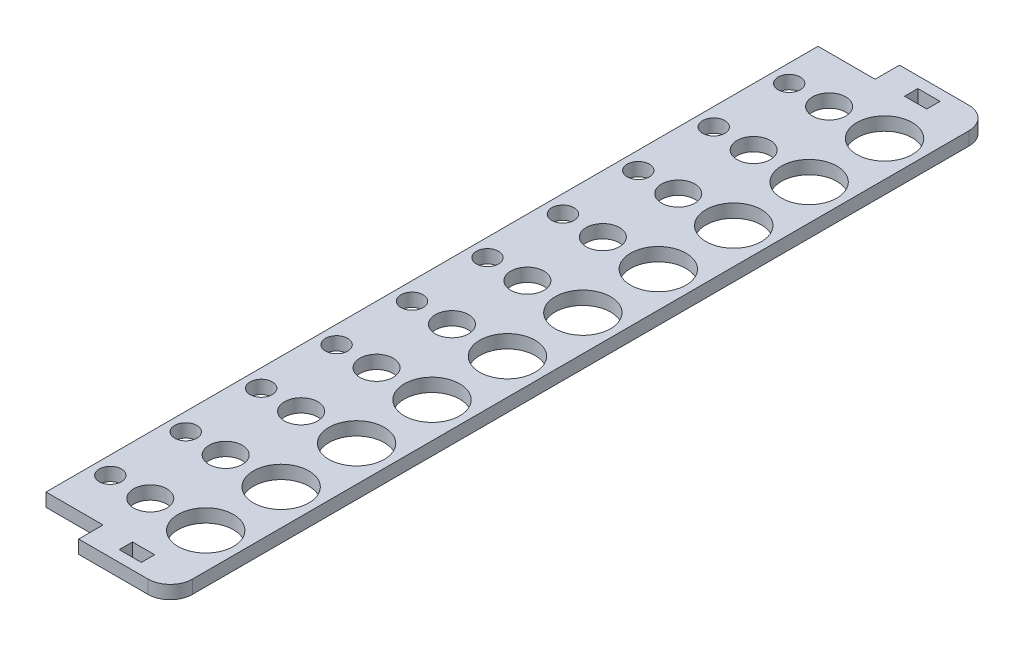
SolidWorks part; units mm, degrees
ref_plane "Plan de face" through (0, 0, 0) normal (0, 0, 1) x (1, 0, 0)
ref_plane "Plan de dessus" through (0, 0, 0) normal (0, 1, 0) x (1, 0, 0)
ref_plane "Plan de droite" through (0, 0, 0) normal (1, 0, 0) x (0, 0, -1)
sketch "Esquisse1" plane through (0, 0, 0) normal (0, 1, 0) x (1, 0, 0)
  line L0 (0, 185) -> (67, 185) construction
  line L1 (0, 11) -> (0, 359)
  line L2 (25.7287, 0) -> (67, 0)
  line L3 (25.7287, 370) -> (67, 370)
  line L4 (67, 0) -> (67, 370)
  line L5 (39, 365) -> (49, 365)
  line L6 (39, 365) -> (39, 359)
  line L7 (39, 359) -> (49, 359)
  line L8 (49, 365) -> (49, 359)
  line L9 (49, 5) -> (49, 11)
  line L10 (39, 11) -> (49, 11)
  line L11 (39, 5) -> (39, 11)
  line L12 (39, 5) -> (49, 5)
  line L13 (25.7287, 370) -> (25.7287, 359)
  line L14 (25.7287, 359) -> (0, 359)
  line L15 (67, 370) -> (66.5533, 370.0668)
  line L16 (25.7287, 0) -> (25.7287, 11)
  line L17 (25.7287, 11) -> (0, 11)
  dimension "D1" = 370
  dimension "D2" = 5
  dimension "D3" = 10
  dimension "D4" = 6
  dimension "D5" = 18
  dimension "D6" = 11
extrude "Boss.-Extru.1" add sketch "Esquisse1" along normal blind 6 contours L1 L0 L4 L3 L13 L14 L5 L8 L7 L6 | L0 L1 L17 L16 L2 L4 L12 L11 L10 L9
sketch "Esquisse2" plane through (0, 6, 0) normal (0, 1, 0) x (1, 0, 0)
  line L0 (67, 0) -> (67, 370) construction
  line L1 (25.7287, 370) -> (67, 370) construction
  line L5 (25.7287, 0) -> (67, 0) construction
  circle A0 centre (51, 338) radius 12.5
  circle A1 centre (51, 304) radius 12.5
  circle A2 centre (51, 270) radius 12.5
  circle A3 centre (51, 236) radius 12.5
  circle A4 centre (51, 202) radius 12.5
  circle A5 centre (51, 168) radius 12.5
  circle A6 centre (51, 134) radius 12.5
  circle A7 centre (51, 100) radius 12.5
  circle A8 centre (51, 66) radius 12.5
  circle A9 centre (26, 338) radius 7.5
  circle A10 centre (8, 338) radius 5
  circle A11 centre (26, 304) radius 7.5
  circle A12 centre (8, 304) radius 5
  circle A13 centre (26, 270) radius 7.5
  circle A14 centre (8, 270) radius 5
  circle A15 centre (26, 236) radius 7.5
  circle A16 centre (8, 236) radius 5
  circle A17 centre (26, 202) radius 7.5
  circle A18 centre (8, 202) radius 5
  circle A19 centre (26, 168) radius 7.5
  circle A20 centre (8, 168) radius 5
  circle A21 centre (26, 134) radius 7.5
  circle A22 centre (8, 134) radius 5
  circle A23 centre (26, 100) radius 7.5
  circle A24 centre (8, 100) radius 5
  circle A25 centre (26, 66) radius 7.5
  circle A26 centre (8, 66) radius 5
  circle A27 centre (26, 32) radius 7.5
  circle A28 centre (8, 32) radius 5
  circle A29 centre (51, 32) radius 12.5
  dimension "D1" = 25
  dimension "D2" = 16
  dimension "D3" = 32
  dimension "D5" = 32
  dimension "D6" = 15
  dimension "D7" = 25
  dimension "D8" = 10
  dimension "D9" = 18
  dimension "D4" = 10
  dimension "D10" = 10
extrude "Enlèv. mat.-Extru.1" cut sketch "Esquisse2" against normal blind 6
fillet "Congé1" radius 10 2 edges at (67, 3, -370) (67, 3, 0)
